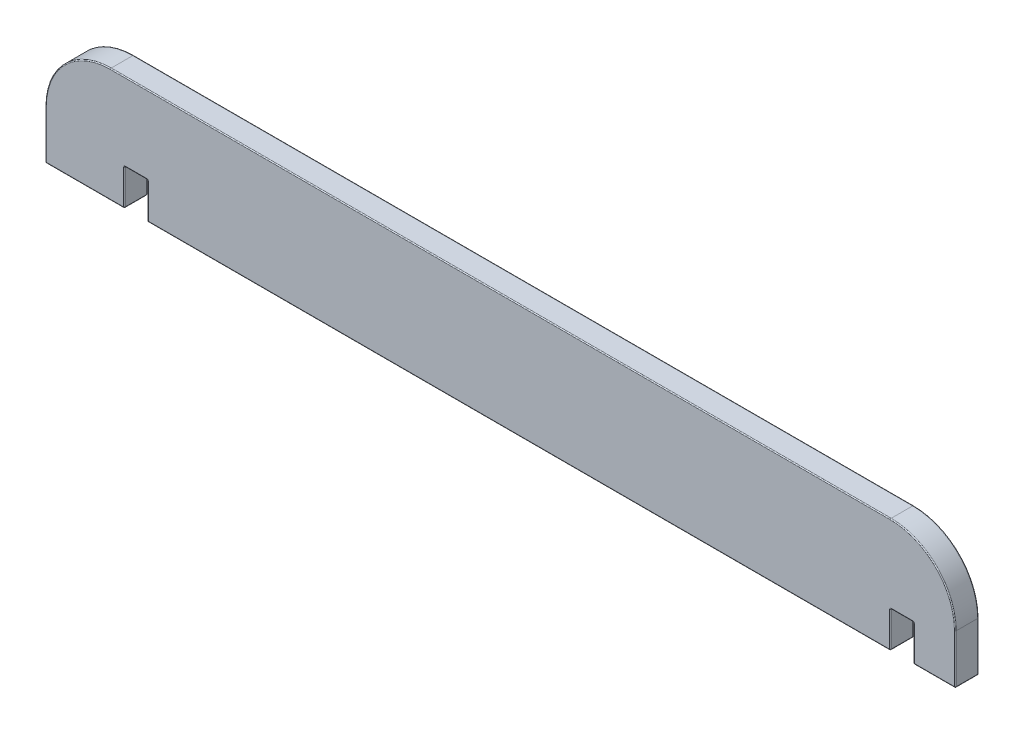
SolidWorks part; units mm, degrees
ref_plane "Plano frontal" through (0, 0, 0) normal (0, 0, 1) x (1, 0, 0)
ref_plane "Plano superior" through (0, 0, 0) normal (0, 1, 0) x (1, 0, 0)
ref_plane "Plano direito" through (0, 0, 0) normal (1, 0, 0) x (0, 0, -1)
sketch "Esboço1" plane through (0, 0, 0) normal (0, 0, 1) x (1, 0, 0)
  line L1 (60.5239, -100.759) -> (158.5239, -100.759)
  line L2 (60.5239, -100.759) -> (60.5239, -95.459)
  line L3 (67.5239, -88.459) -> (151.5239, -88.459)
  line L4 (158.5239, -100.759) -> (158.5239, -95.459)
  line L5 (69.0239, -100.759) -> (71.5239, -100.759)
  line L6 (69.0239, -100.759) -> (69.0239, -96.859)
  line L7 (69.0239, -96.859) -> (71.5239, -96.859)
  line L8 (71.5239, -100.759) -> (71.5239, -96.859)
  line L9 (154.0239, -100.759) -> (151.5239, -100.759)
  line L10 (154.0239, -100.759) -> (154.0239, -96.859)
  line L11 (154.0239, -96.859) -> (151.5239, -96.859)
  line L12 (151.5239, -100.759) -> (151.5239, -96.859)
  arc A0 (151.5239, -88.459) -> (158.5239, -95.459) centre (151.5239, -95.459) cw
  arc A1 (60.5239, -95.459) -> (67.5239, -88.459) centre (67.5239, -95.459) cw
  point P16 (109.5239, -100.759)
  dimension "D1" = 7
  dimension "D2" = 80
  dimension "D3" = 98
  dimension "D4" = 42
  dimension "D5" = 2.5
  dimension "D6" = 3.9
  dimension "D7" = 12.3
extrude "Ressalto-extrusão1" add sketch "Esboço1" along normal blind 2.5 contours A1 L2 L1 L6 L7 L8 L12 L11 L10 L4 A0 L3
fillet "Filete1" radius 0.1 38 edges at (60.5239, -100.759, 1.25) (69.0239, -100.759, 1.25) (69.0239, -96.859, 1.25) (71.5239, -96.859, 1.25) (71.5239, -100.759, 1.25) (151.5239, -100.759, 1.25) (151.5239, -96.859, 1.25) (154.0239, -96.859, 1.25) (154.0239, -100.759, 1.25) (158.5239, -100.759, 1.25) (109.5239, -88.459, 2.5) (156.4736, -90.5093, 2.5) (158.5239, -98.109, 2.5) (156.2739, -100.759, 2.5) (154.0239, -98.809, 2.5) (152.7739, -96.859, 2.5) (151.5239, -98.809, 2.5) (111.5239, -100.759, 2.5) (71.5239, -98.809, 2.5) (70.2739, -96.859, 2.5) (69.0239, -98.809, 2.5) (64.7739, -100.759, 2.5) (60.5239, -98.109, 2.5) (62.5741, -90.5093, 2.5) (60.5239, -98.109, 0) (64.7739, -100.759, 0) (69.0239, -98.809, 0) (70.2739, -96.859, 0) (71.5239, -98.809, 0) (111.5239, -100.759, 0) (151.5239, -98.809, 0) (152.7739, -96.859, 0) (154.0239, -98.809, 0) (156.2739, -100.759, 0) (158.5239, -98.109, 0) (156.4736, -90.5093, 0) (109.5239, -88.459, 0) (62.5741, -90.5093, 0)
